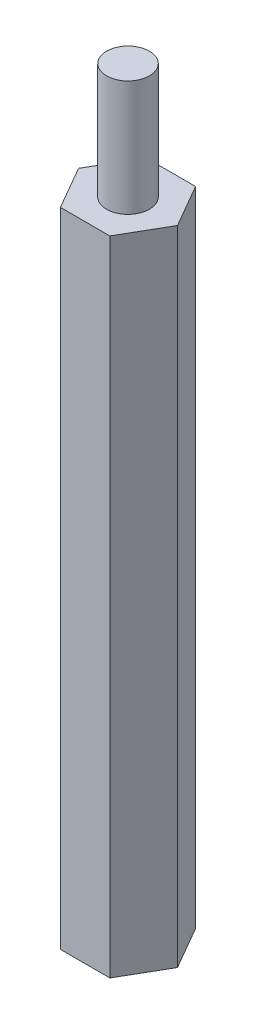
SolidWorks part; units mm, degrees
ref_plane "Front Plane" through (0, 0, 0) normal (0, 0, 1) x (1, 0, 0)
ref_plane "Top Plane" through (0, 0, 0) normal (0, 1, 0) x (1, 0, 0)
ref_plane "Right Plane" through (0, 0, 0) normal (1, 0, 0) x (0, 0, -1)
sketch "Sketch3" plane through (0, 0, 0) normal (0, 1, 0) x (1, 0, 0)
  line L1 (-3.4641, 0) -> (-1.7321, -3)
  line L2 (-1.7321, -3) -> (1.7321, -3)
  line L3 (1.7321, -3) -> (3.4641, 0)
  line L4 (3.4641, 0) -> (1.7321, 3)
  line L5 (1.7321, 3) -> (-1.7321, 3)
  line L6 (-1.7321, 3) -> (-3.4641, 0)
  circle A0 centre (0, 0) radius 3 construction
  dimension "D1" = 6
extrude "Boss-Extrude1" add sketch "Sketch3" along normal blind 45
sketch "Sketch5" plane through (0, 45, 0) normal (0, 1, 0) x (1, 0, 0)
  circle A0 centre (0, 0) radius 1.5
  dimension "D1" = 3
extrude "Boss-Extrude2" add sketch "Sketch5" along normal blind 8.0916
sketch "Sketch6" plane through (0, 0, 0) normal (0, -1, 0) x (1, 0, 0)
  circle A0 centre (0, 0) radius 1.5
extrude "Cut-Extrude1" cut sketch "Sketch6" against normal blind 4
